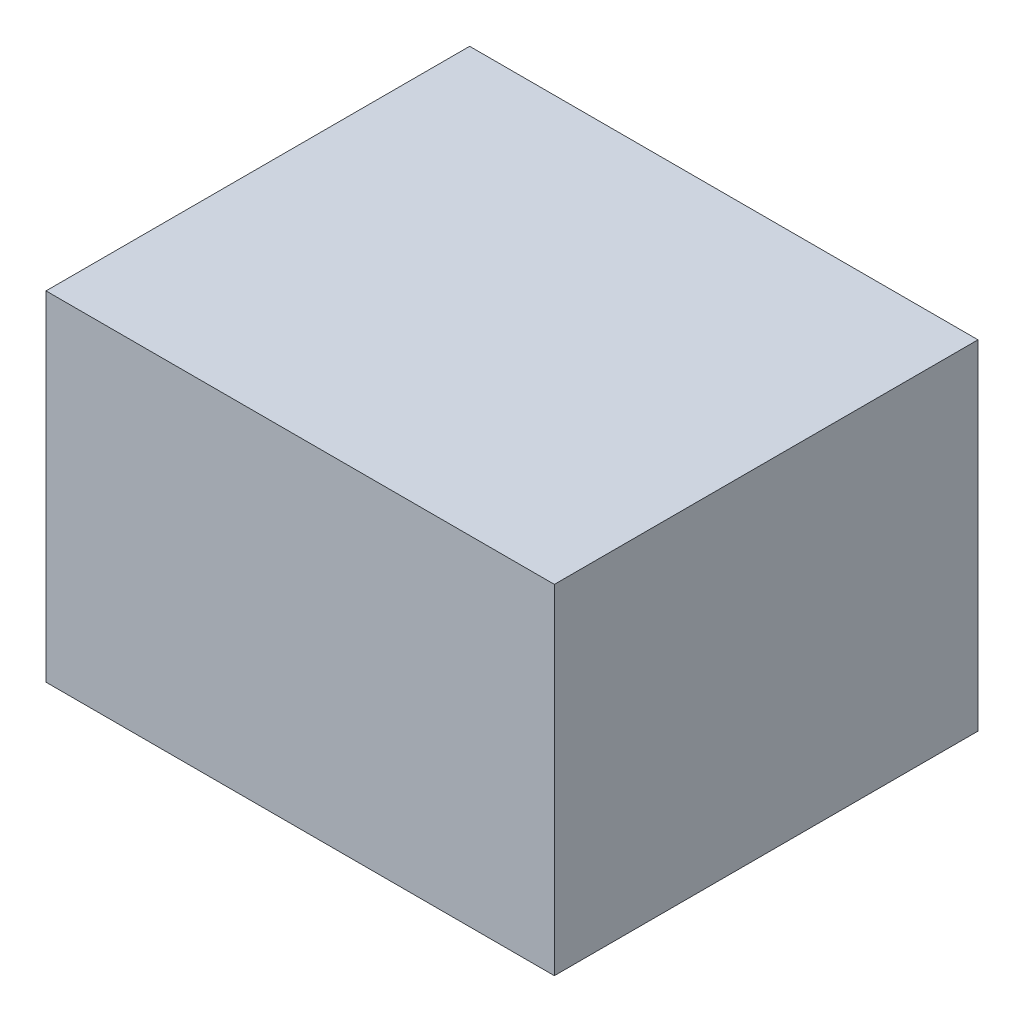
SolidWorks part; units mm, degrees
ref_plane "Front Plane" through (0, 0, 0) normal (0, 0, 1) x (1, 0, 0)
ref_plane "Top Plane" through (0, 0, 0) normal (0, 1, 0) x (1, 0, 0)
ref_plane "Right Plane" through (0, 0, 0) normal (1, 0, 0) x (0, 0, -1)
sketch "Sketch1" plane through (0, 0, 0) normal (0, 1, 0) x (1, 0, 0)
  line L1 (-60, 50) -> (60, 50)
  line L2 (-60, 50) -> (-60, -50)
  line L3 (-60, -50) -> (60, -50)
  line L4 (60, 50) -> (60, -50)
  line L5 (-60, 50) -> (60, -50) construction
  line L6 (-60, -50) -> (60, 50) construction
  point P0 (0, 0)
  dimension "D1" = 120
  dimension "D2" = 100
extrude "Boss-Extrude1" add sketch "Sketch1" along normal blind 80
